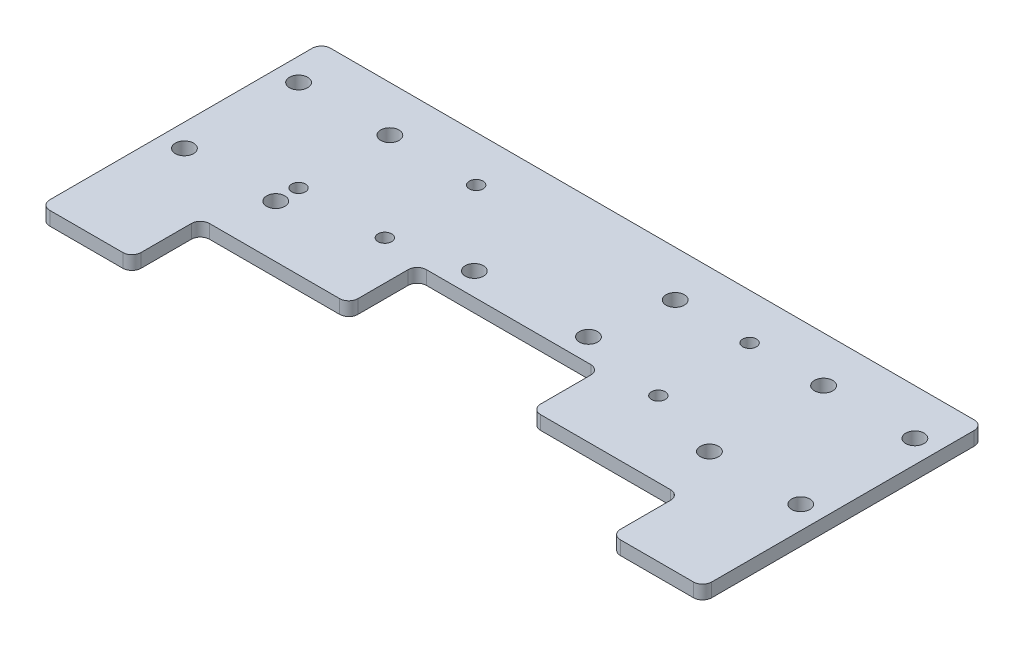
SolidWorks part; units mm, degrees
material "Thornel Mat VMA"
ref_plane "前视基准面" through (0, 0, 0) normal (0, 0, 1) x (1, 0, 0)
ref_plane "上视基准面" through (0, 0, 0) normal (0, 1, 0) x (1, 0, 0)
ref_plane "右视基准面" through (0, 0, 0) normal (1, 0, 0) x (0, 0, -1)
other "Configuration Table"
sketch "草图1" plane through (0, 0, 0) normal (0, 1, 0) x (1, 0, 0)
  line L0 (-72.5, 22.5) -> (-72.5, -39)
  line L1 (67.5, -12.5) -> (-67.5, -12.5) construction
  line L2 (67.5, -12.5) -> (67.5, 12.5) construction
  line L3 (67.5, 12.5) -> (-67.5, 12.5) construction
  line L4 (-67.5, -12.5) -> (-67.5, 12.5) construction
  line L5 (67.5, -12.5) -> (-67.5, 12.5) construction
  line L6 (67.5, 12.5) -> (-67.5, -12.5) construction
  line L7 (15, -12.5) -> (-80, -12.5) construction
  line L8 (15, -12.5) -> (15, 12.5) construction
  line L9 (15, 12.5) -> (-79.9037, 12.5) construction
  line L10 (-80, -12.5) -> (-80, 12.5) construction
  line L11 (15, -12.5) -> (-80, 12.5) construction
  line L12 (15, 12.5) -> (-80, -12.5) construction
  line L13 (72.5, 22.5) -> (-72.5, 22.5)
  line L14 (72.5, 22.5) -> (72.5, -39)
  line L15 (72.5, -39) -> (-72.5, -39)
  line L17 (72.5, 22.5) -> (-72.5, -33.2716) construction
  line L18 (72.5, -39) -> (-72.5, 16.7716) construction
  line L19 (47.5, -12.5) -> (-47.5, -12.5) construction
  line L20 (47.5, -12.5) -> (47.5, 12.5) construction
  line L21 (47.5, 12.5) -> (-47.5, 12.5) construction
  line L22 (-47.5, -12.5) -> (-47.5, 12.5) construction
  line L23 (47.5, -12.5) -> (-47.5, 12.5) construction
  line L24 (47.5, 12.5) -> (-47.5, -12.5) construction
  circle A0 centre (-67.5, 12.5) radius 2
  circle A1 centre (-67.5, -12.5) radius 2
  circle A2 centre (67.5, 12.5) radius 2
  circle A3 centre (67.5, -12.5) radius 2
  circle A6 centre (15, 12.5) radius 2
  circle A7 centre (15, -12.5) radius 2
  circle A8 centre (-47.5, 12.5) radius 2
  circle A9 centre (-47.5, -12.5) radius 2
  circle A10 centre (47.5, 12.5) radius 2
  circle A11 centre (47.5, -12.5) radius 2
  point P0 (0, 0)
  point P10 (-32.5, 0)
  point P19 (0, 0)
  point P24 (0, 0)
  dimension "D3" = 4
  dimension "D12" = 95
  dimension "D4" = 145
  dimension "D1" = 135
  dimension "D2" = 25
  dimension "D5" = 25
  dimension "D6" = 12.5
  dimension "D8" = 5
  dimension "D10" = 10
  dimension "D11" = 61.5
extrude "凸台-拉伸1" add sketch "草图1" along normal blind 3
sketch "草图2" plane through (0, 3, 0) normal (0, 1, 0) x (1, 0, 0)
  line L0 (-52.5, -39) -> (-52.5, -24)
  line L1 (-72.5, -39) -> (72.5, -39) construction
  line L3 (52.5, -24) -> (52.5, -39)
  line L4 (52.5, -39) -> (-52.5, -39)
  line L5 (0, 0) -> (0, 48.6166) construction
  line L6 (-20, -9) -> (-20, -24)
  line L7 (-20, -9) -> (20, -9)
  line L8 (20, -9) -> (20, -24)
  line L10 (0, -9) -> (0, 5.7876) construction
  line L11 (20, -24) -> (52.5, -24)
  line L12 (-52.5, -24) -> (-20, -24)
  circle A1 centre (-12.5, -4) radius 2
  circle A3 centre (12.5, -4) radius 2
  dimension "D6" = 12.5
  dimension "D7" = 4
  dimension "D1" = 105
  dimension "D2" = 15
  dimension "D3" = 15
  dimension "D4" = 40
  dimension "D8" = 5
extrude "切除-拉伸1" cut sketch "草图2" against normal blind 10
sketch "草图3" plane through (0, 3, 0) normal (0, 1, 0) x (1, 0, 0)
  line L0 (72.5, 22.5) -> (-72.5, 22.5) construction
  line L2 (-52.5, -24) -> (-52.5, -39) construction
  circle A0 centre (-47.5, 12.5) radius 1.5
  circle A1 centre (-47.5, -7.5) radius 1.5
  circle A2 centre (31.3, 12.5) radius 1.5
  circle A3 centre (31.3, -7.5) radius 1.5
  circle A4 centre (-28.6, 12.5) radius 1.5
  circle A5 centre (-28.6, -7.5) radius 1.5
  dimension "D2" = 3
  dimension "D5" = 78.8
  dimension "D1" = 20
  dimension "D3" = 10
  dimension "D4" = 5
  dimension "D6" = 2
extrude "切除-拉伸2" cut sketch "草图3" against normal blind 10
fillet "圆角2" radius 2 12 edges at (-52.5, 1.5, 39) (72.5, 1.5, -22.5) (72.5, 1.5, 39) (52.5, 1.5, 39) (52.5, 1.5, 24) (20, 1.5, 24) (20, 1.5, 9) (-20, 1.5, 9) (-20, 1.5, 24) (-52.5, 1.5, 24) (-72.5, 1.5, 39) (-72.5, 1.5, -22.5)
